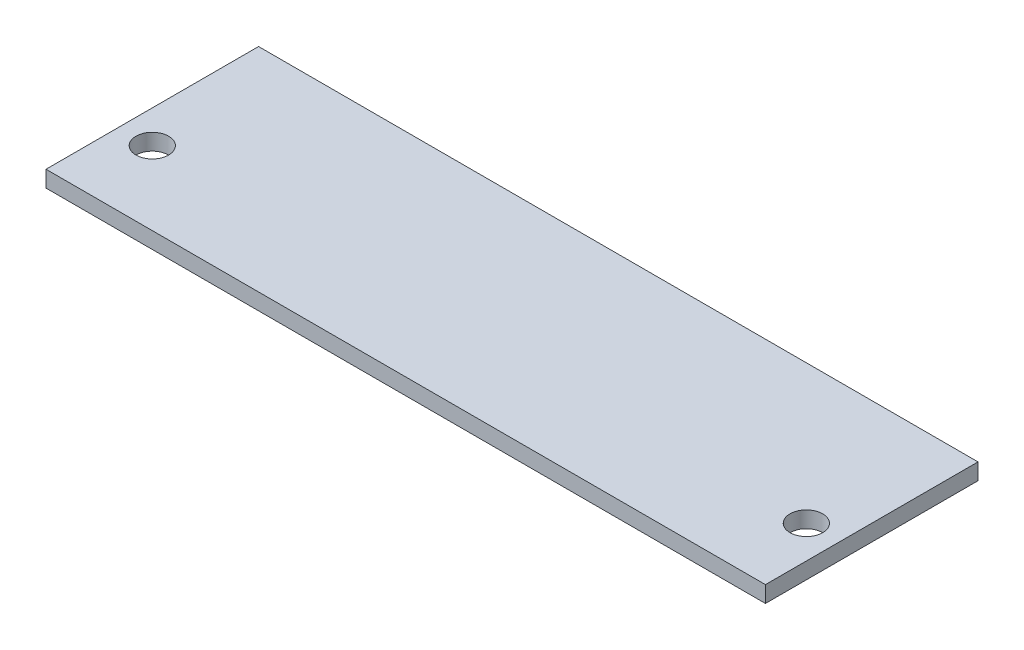
SolidWorks part; units mm, degrees
material "ASTM A36 Steel"
ref_plane "Front Plane" through (0, 0, 0) normal (0, 0, 1) x (1, 0, 0)
ref_plane "Top Plane" through (0, 0, 0) normal (0, 1, 0) x (1, 0, 0)
ref_plane "Right Plane" through (0, 0, 0) normal (1, 0, 0) x (0, 0, -1)
sketch "Sketch2" plane through (0, 0, 0) normal (0, 1, 0) x (1, 0, 0)
  line L1 (0, 0) -> (279.4, 0)
  line L2 (0, 0) -> (0, -82.55)
  line L3 (0, -82.55) -> (279.4, -82.55)
  line L4 (279.4, 0) -> (279.4, -82.55)
  circle A0 centre (12.7, -53.9732) radius 6.35
  circle A1 centre (266.7, -53.9732) radius 6.35
  point P13 (144.2128, -74.4587)
  dimension "D3" = 12.7
  dimension "D6" = 12.7
  dimension "D1" = 279.4
  dimension "D2" = 82.55
  dimension "D4" = 12.7
  dimension "D5" = 53.9732
  dimension "D7" = 12.7
  dimension "D8" = 53.9732
extrude "Boss-Extrude1" add sketch "Sketch2" along normal blind 6.35
